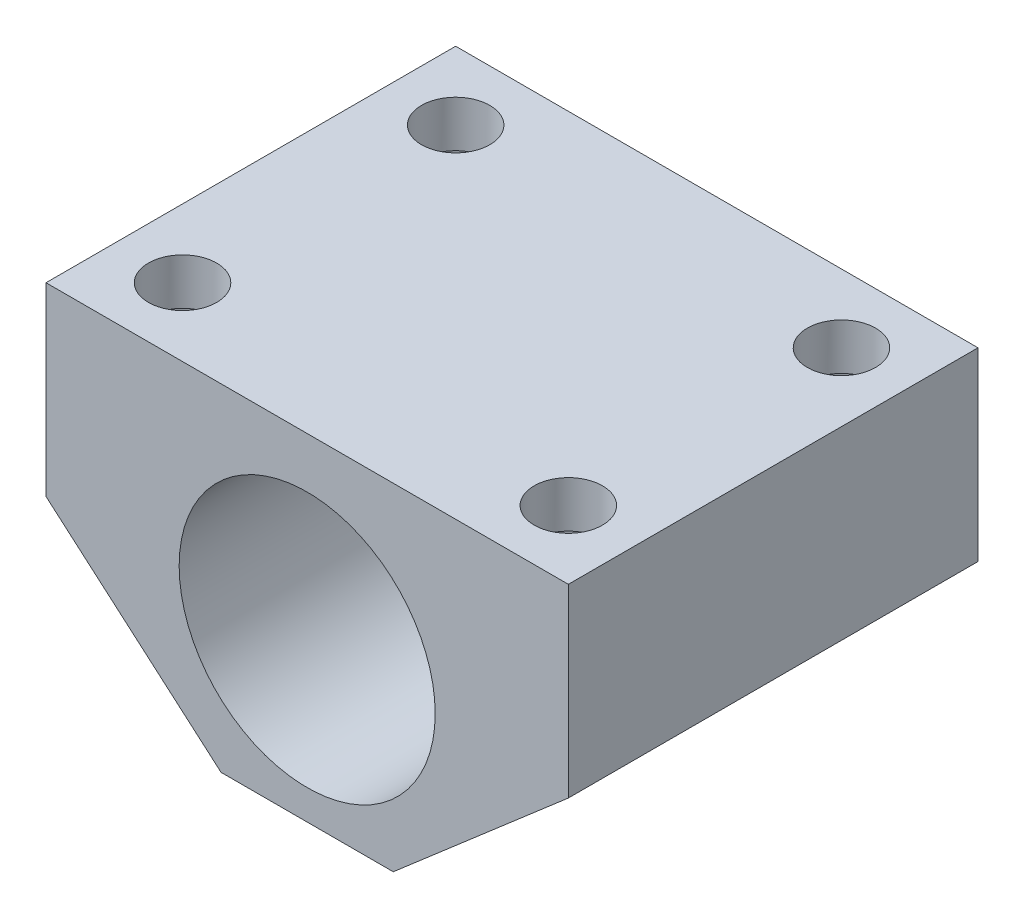
SolidWorks part; units mm, degrees
ref_plane "Plan de face" through (0, 0, 0) normal (0, 0, 1) x (1, 0, 0)
ref_plane "Plan de dessus" through (0, 0, 0) normal (0, 1, 0) x (1, 0, 0)
ref_plane "Plan de droite" through (0, 0, 0) normal (1, 0, 0) x (0, 0, -1)
sketch "Esquisse1" plane through (0, 0, 0) normal (0, 0, 1) x (1, 0, 0)
  line L0 (15.301, 10.4669) -> (-15.301, 10.4669)
  line L1 (-15.301, 10.4669) -> (-15.301, -0.3783)
  line L2 (-15.301, -0.3783) -> (-5.0443, -9.2478)
  line L3 (-5.0443, -9.2478) -> (5.0443, -9.2478)
  line L4 (0, -9.2478) -> (0, -7.5)
  line L5 (0, 7.5) -> (0, 10.4669)
  line L6 (15.301, -0.3783) -> (5.0443, -9.2478)
  line L7 (15.301, 10.4669) -> (15.301, -0.3783)
  arc A1 (0, 7.5) -> (0, -7.5) centre (0, 0) ccw construction
  circle A3 centre (0, 0) radius 7.5
extrude "Boss.-Extru.1" add sketch "Esquisse1" along normal mid plane 24 contours A3 L4 L3 L6 L7 L0 L5 | A3 L5 L0 L1 L2 L3 L4
sketch "Esquisse2" plane through (0, 10.4669, 0) normal (0, 1, 0) x (1, 0, 0)
  line L0 (-15.301, -12) -> (-15.301, 12) construction
  line L2 (15.301, -12) -> (15.301, 12) construction
  line L3 (15.301, 12) -> (-15.301, 12) construction
  line L4 (15.301, -12) -> (-15.301, -12) construction
  circle A0 centre (-11.301, 8) radius 2
  circle A1 centre (-11.301, -8) radius 2
  circle A2 centre (11.301, -8) radius 2
  circle A3 centre (11.301, 8) radius 2
  point P8 (0, 0)
  point P9 (0, 0)
  point P10 (0, 0)
  point P11 (0, 0)
  dimension "D1" = 4
  dimension "D4" = 4
  dimension "D5" = 4
  dimension "D2" = 4
  dimension "D3" = 4
extrude "Enlèv. mat.-Extru.1" cut sketch "Esquisse2" against normal through all
sketch "Esquisse4" plane through (0, -9.2478, 0) normal (0, -1, 0) x (1, 0, 0)
  circle A6 centre (-11.301, 8) radius 3.7
  circle A9 centre (-11.301, -8) radius 3.7
  circle A12 centre (11.301, 8) radius 3.7
  circle A14 centre (11.301, -8) radius 3.7
  circle A15 centre (11.301, -8) radius 3.7
  dimension "D4" = 1.7
extrude "Enlèv. mat.-Extru.2" cut sketch "Esquisse4" against normal blind 17
